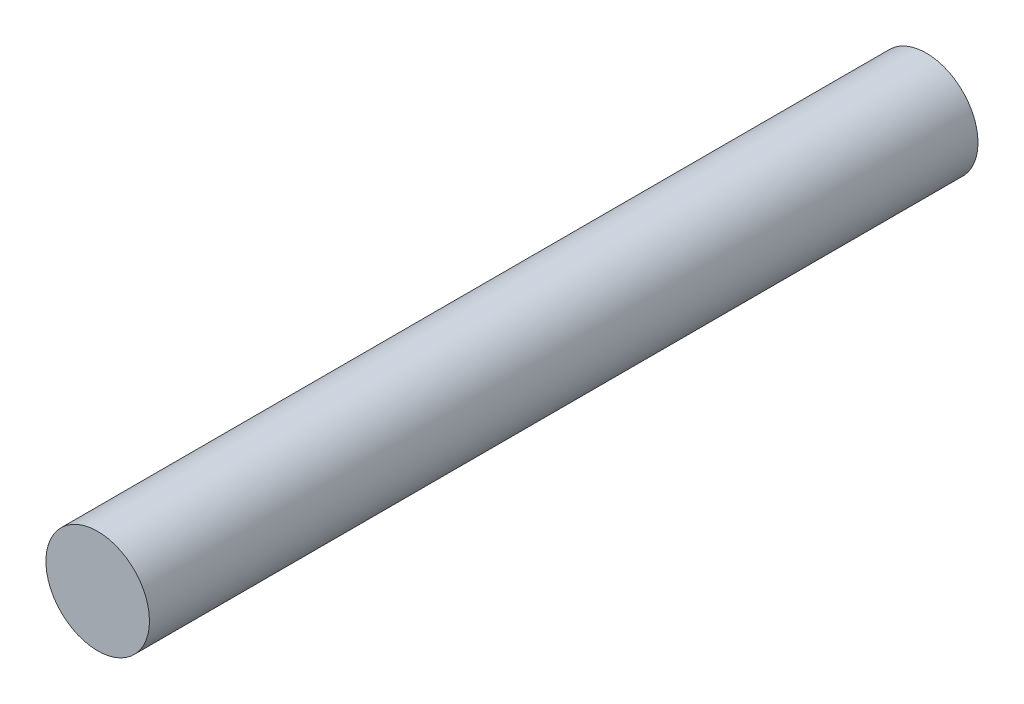
SolidWorks part; units mm, degrees
ref_plane "Front Plane" through (0, 0, 0) normal (0, 0, 1) x (1, 0, 0)
ref_plane "Top Plane" through (0, 0, 0) normal (0, 1, 0) x (1, 0, 0)
ref_plane "Right Plane" through (0, 0, 0) normal (1, 0, 0) x (0, 0, -1)
sketch "Sketch1" plane through (0, 0, 0) normal (0, 0, 1) x (1, 0, 0)
  circle A0 centre (0, 0) radius 1.5875
  dimension "D1" = 3.175
extrude "Boss-Extrude1" add sketch "Sketch1" along normal blind 25.4 contours A0
equation "\"Do\"= 0.25"
equation "\"Di\"= .125"
equation "\"L1\"= 1"
equation "\"t\"= 0.9375 / ( 2 * \"Do\" * 1000 )"
equation "\"ODo\"= ( 2 * \"t\" ) + \"Do\""
equation "\"ODi\"= ( 2 * \"t\" ) + \"Di\""
equation "\"D1@Sketch1\"= \"Di\""
equation "\"D1@Boss-Extrude1\"= \"L1\""
